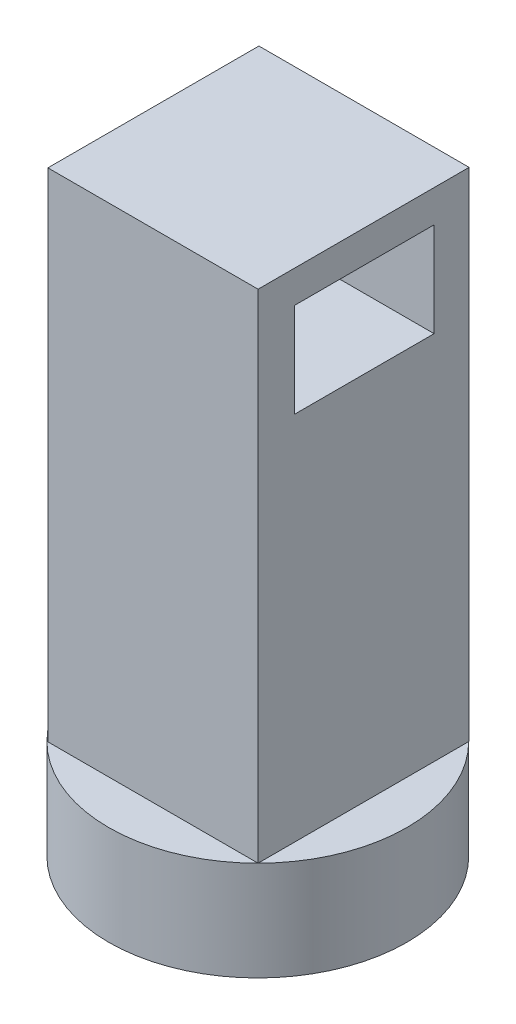
SolidWorks part; units mm, degrees
ref_plane "Front Plane" through (0, 0, 0) normal (0, 0, 1) x (1, 0, 0)
ref_plane "Top Plane" through (0, 0, 0) normal (0, 1, 0) x (1, 0, 0)
ref_plane "Right Plane" through (0, 0, 0) normal (1, 0, 0) x (0, 0, -1)
sketch "Sketch1" plane through (0, 0, 0) normal (0, 1, 0) x (1, 0, 0)
  circle A0 centre (0, 0) radius 3.81
extrude "Boss-Extrude1" add sketch "Sketch1" along normal blind 2.54
sketch "Sketch2" plane through (0, 0, 0) normal (0, -1, 0) x (1, 0, 0)
  circle A0 centre (0, 0) radius 1.905
extrude "Cut-Extrude2" cut sketch "Sketch2" against normal blind 1.27
sketch "Sketch3" plane through (0, 2.54, 0) normal (0, 1, 0) x (1, 0, 0)
  line L5 (-2.672, 2.7006) -> (2.6975, 2.7006)
  line L6 (-2.672, 2.7006) -> (-2.672, -2.6906)
  line L7 (-2.672, -2.6906) -> (2.6975, -2.6906)
  line L8 (2.6975, 2.7006) -> (2.6975, -2.6906)
  circle A0 centre (0, 0) radius 3.81 construction
extrude "Boss-Extrude2" add sketch "Sketch3" along normal blind 12.7 contours L6 L5 L8 L7
sketch "Sketch4" plane through (2.6975, 0, 0) normal (1, 0, 0) x (0, 0, -1)
  line L1 (-1.7545, 14.4158) -> (1.8068, 14.4158)
  line L2 (-1.7545, 14.4158) -> (-1.7545, 12.0071)
  line L3 (-1.7545, 12.0071) -> (1.8068, 12.0071)
  line L4 (1.8068, 14.4158) -> (1.8068, 12.0071)
extrude "Cut-Extrude3" cut sketch "Sketch4" against normal blind 12.7
